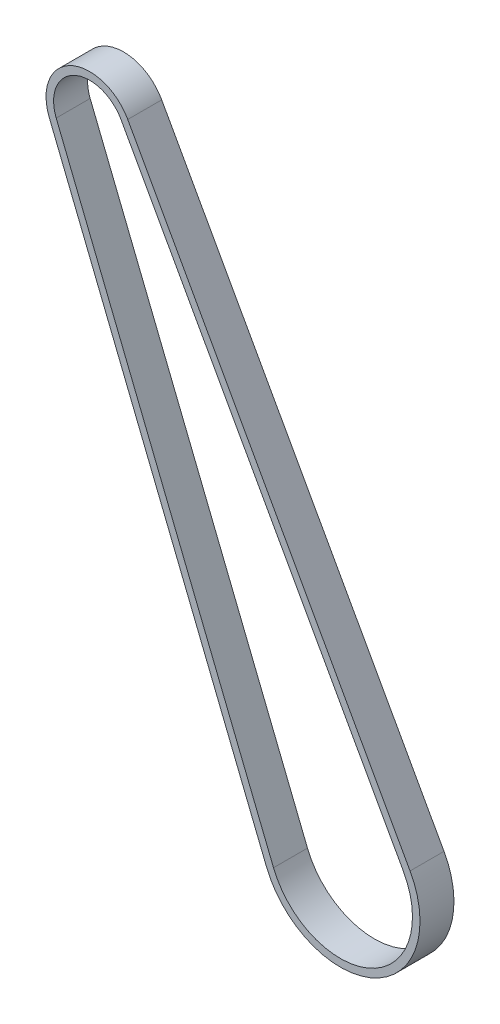
SolidWorks part; units mm, degrees
material "NEOPRENE"
ref_plane "Front" through (0, 0, 0) normal (0, 0, 1) x (1, 0, 0)
ref_plane "Top" through (0, 0, 0) normal (0, 1, 0) x (1, 0, 0)
ref_plane "Right" through (0, 0, 0) normal (1, 0, 0) x (0, 0, -1)
sketch "Sketch2" plane through (0, 0, 0) normal (0, 0, 1) x (1, 0, 0)
  line L0 (0, 0) -> (1, 0) construction
  line L1 (0, 0) -> (0, 1) construction
  line L2 (8.3547, 4.6271) -> (83.1621, -130.4459)
  line L3 (48.7304, -146.8244) -> (-8.8612, -3.5622)
  arc A0 (-8.8612, -3.5622) -> (8.3547, 4.6271) centre (0, 0) cw
  arc A1 (83.1621, -130.4459) -> (48.7304, -146.8244) centre (66.4528, -139.7) cw
extrude "Extrude-Thin1" add sketch "Sketch2" along normal mid plane 9 thin thin type one direction wall 2
